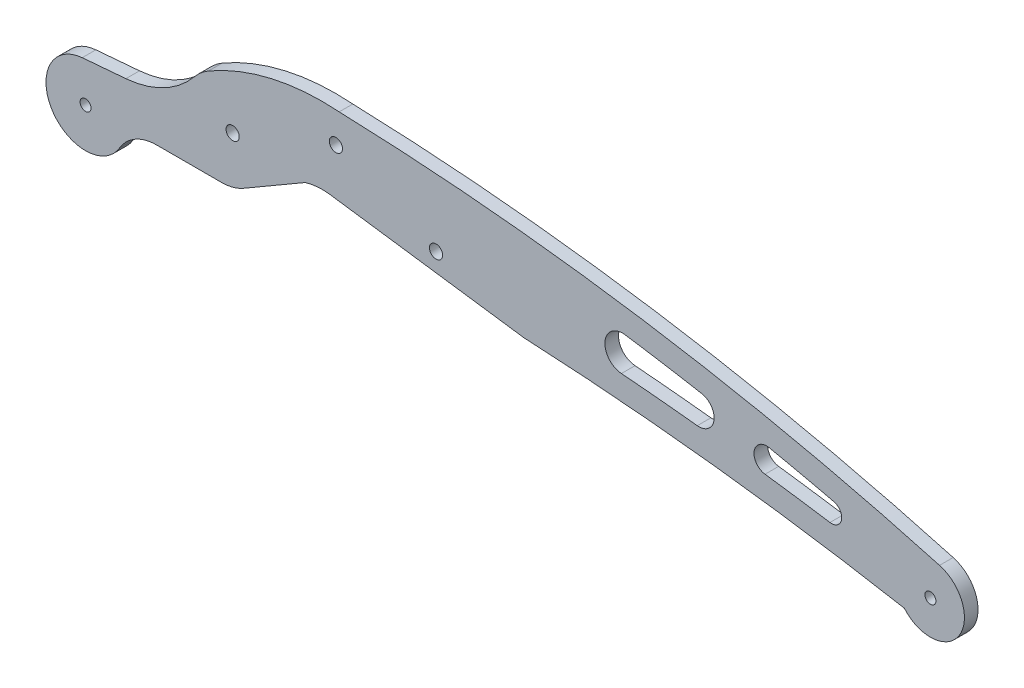
SolidWorks part; units mm, degrees
ref_plane "Front Plane" through (0, 0, 0) normal (0, 0, 1) x (1, 0, 0)
ref_plane "Top Plane" through (0, 0, 0) normal (0, 1, 0) x (1, 0, 0)
ref_plane "Right Plane" through (0, 0, 0) normal (1, 0, 0) x (0, 0, -1)
sketch "Sketch1" plane through (0, 0, 0) normal (0, 0, 1) x (1, 0, 0)
  line L0 (85.6, -33.2) -> (-2.7185, -20.8785)
  line L1 (-14, -21.8) -> (-42.0398, -38.0927)
  line L2 (-52.0878, -40.8) -> (-81.6991, -40.8)
  line L4 (-115.5, -23.3126) -> (-95.6181, -21.65)
  line L9 (86.6343, -22.2378) -> (-1.1986, -9.984) construction
  line L10 (-18.5488, -11.7209) -> (-47.5662, -28.5817) construction
  line L11 (-52.0878, -29.8) -> (-81.6991, -29.8) construction
  line L12 (-114.5833, -34.2743) -> (-94.7014, -32.6117) construction
  circle A0 centre (-114, -41.25) radius 2.5
  circle A1 centre (270.7, -43.25) radius 2.5
  circle A2 centre (-47, -18.8) radius 3
  circle A3 centre (45.6, -19.2) radius 3
  circle A4 centre (0, 0) radius 3
  circle A5 centre (-114, -41.25) radius 4 construction
  circle A6 centre (270.7, -43.25) radius 3 construction
  arc A15 (258.8573, -53.25) -> (85.6, -33.2) centre (20.2413, -1356.587) ccw
  arc A16 (-2.7185, -20.8785) -> (-14, -21.8) centre (-6.3, -46.55) ccw
  arc A17 (-81.6991, -40.8) -> (-98.4956, -50.394) centre (-81.6991, -60.3) ccw
  arc A18 (-115.5, -23.3126) -> (-98.4956, -50.394) centre (-114, -41.25) ccw
  arc A20 (-95.6181, -21.65) -> (-64.3414, -5.2) centre (-99.3924, 23.4848) ccw
  arc A21 (1.5, 13.8188) -> (-58, 0.2) centre (-6.3009, -88.8853) ccw
  arc A22 (274.8783, -28.3238) -> (1.5, 13.8188) centre (-36.5716, -1140.9217) ccw
  arc A23 (258.8573, -53.25) -> (274.8783, -28.3238) centre (270.7, -43.25) ccw
  arc A24 (-42.0398, -38.0927) -> (-52.0878, -40.8) centre (-52.0878, -20.8) cw
  arc A25 (-64.3414, -5.2) -> (-58, 0.2) centre (-46.2959, -19.9679) cw
  arc A26 (226.7442, -27.2598) -> (197.0716, -20.6588) centre (-36.5716, -1140.9217) ccw
  arc A34 (224.9645, -36.3657) -> (195.4065, -32.1199) centre (20.2413, -1356.587) ccw
  arc A36 (132.3472, -9.0893) -> (130.0105, -25.1041) centre (130.6, -17.0123) ccw
  arc A37 (166.5349, -14.722) -> (164.5602, -28.4048) centre (165.3074, -21.5287) cw
  arc A38 (197.0716, -20.6588) -> (195.4065, -32.1199) centre (196.1658, -26.3787) ccw
  arc A39 (226.7442, -27.2598) -> (224.9645, -36.3657) centre (225.676, -31.7779) cw
  arc A40 (271.9131, -38.9166) -> (0.8958, 2.8327) centre (-36.5716, -1140.9217) ccw construction
  arc A41 (266.2033, -43.4234) -> (86.6343, -22.2378) centre (20.2413, -1356.587) ccw construction
  arc A42 (266.2033, -43.4234) -> (271.9131, -38.9166) centre (270.7, -43.25) ccw construction
  arc A43 (166.5349, -14.722) -> (132.3472, -9.0893) centre (-36.5716, -1140.9217) ccw
  arc A44 (164.5602, -28.4048) -> (130.0105, -25.1041) centre (20.2413, -1356.587) ccw
  arc A46 (-1.1986, -9.984) -> (-18.5488, -11.7209) centre (-6.3, -46.55) ccw construction
  arc A47 (-47.5662, -28.5817) -> (-52.0878, -29.8) centre (-52.0878, -20.8) cw construction
  arc A48 (0.8958, 2.8327) -> (-52.4787, -9.314) centre (-6.3009, -88.8853) ccw construction
  arc A49 (-94.7014, -32.6117) -> (-55.8286, -12.1666) centre (-99.3924, 23.4848) ccw construction
  arc A50 (-55.8286, -12.1666) -> (-52.4787, -9.314) centre (-46.2959, -19.9679) cw construction
  arc A51 (-81.6991, -29.8) -> (-107.9705, -44.806) centre (-81.6991, -60.3) ccw construction
  arc A52 (-114.5833, -34.2743) -> (-107.9705, -44.806) centre (-114, -41.25) ccw construction
  point P52 (-46.6991, -40.8)
  dimension "D1" = 6
  dimension "D6" = 67
  dimension "D7" = 22.45
  dimension "D8" = 18
  dimension "D9" = 103
  dimension "D14" = 19.5
  dimension "D17" = 20
  dimension "D22" = 5
  dimension "D23" = 15.5
  dimension "D24" = 1325
  dimension "D36" = 8.1133
  dimension "D37" = 2.1877
  dimension "D41" = 11
  dimension "D42" = 5
  dimension "D35" = 35
  dimension "D2" = 18.8
  dimension "D3" = 47
  dimension "D4" = 45.6
  dimension "D5" = 19.2
  dimension "D10" = 46.55
  dimension "D11" = 6.3
  dimension "D12" = 35
  dimension "D13" = 22
  dimension "D15" = 33
  dimension "D16" = 3
  dimension "D18" = 40
  dimension "D19" = 14
  dimension "D20" = 270.7
  dimension "D21" = 43.25
  dimension "D25" = 10
  dimension "D26" = 14.9262
  dimension "D27" = 13.9
  dimension "D28" = 1.5
  dimension "D29" = 11
  dimension "D30" = 19
  dimension "D31" = 1.5
  dimension "D32" = 19.6
  dimension "D33" = 13.6
  dimension "D34" = 85
  dimension "D38" = 30.8584
  dimension "D39" = 4.85
  dimension "D40" = 30
extrude "Boss-Extrude1" add sketch "Sketch1" along normal blind 6.2
